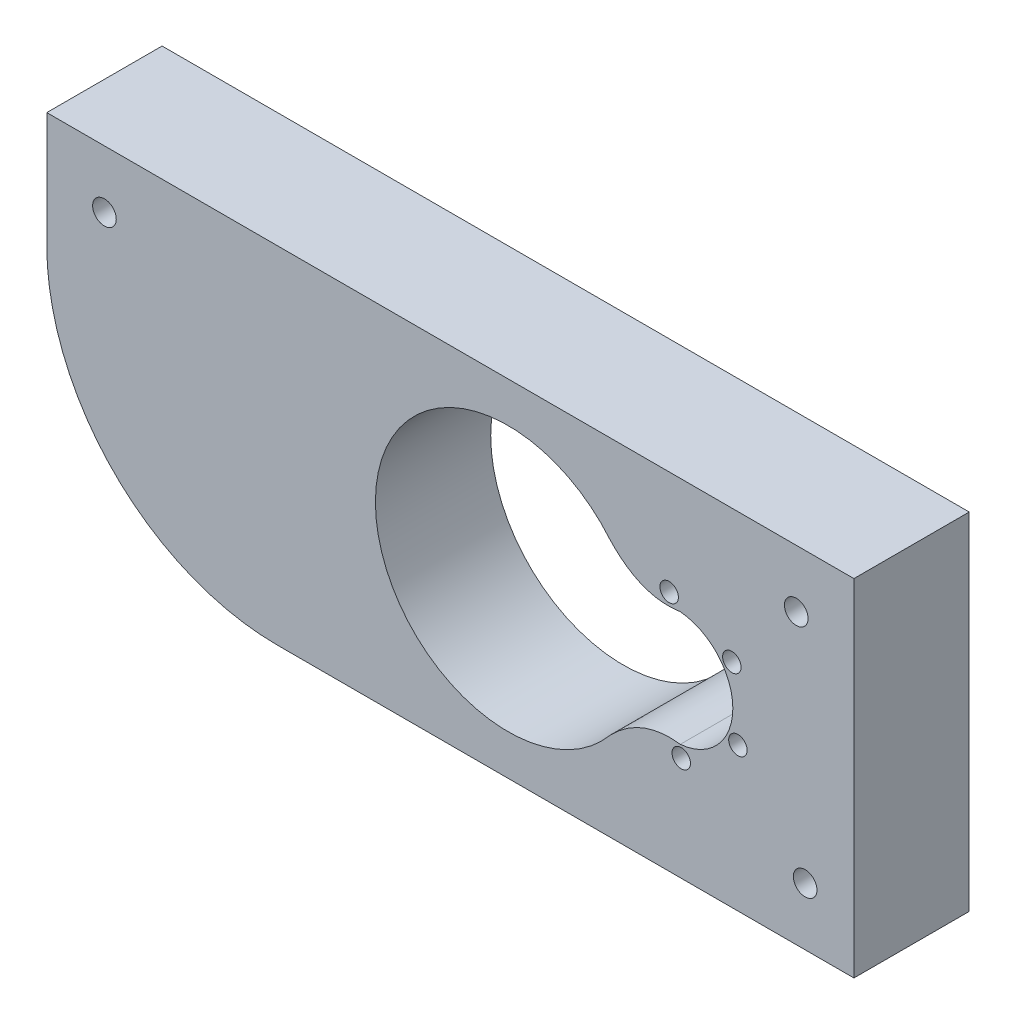
SolidWorks part; units mm, degrees
ref_plane "Plan de face" through (0, 0, 0) normal (0, 0, 1) x (1, 0, 0)
ref_plane "Plan de dessus" through (0, 0, 0) normal (0, 1, 0) x (1, 0, 0)
ref_plane "Plan de droite" through (0, 0, 0) normal (1, 0, 0) x (0, 0, -1)
sketch "Esquisse1" plane through (0, 0, 0) normal (0, 0, 1) x (1, 0, 0)
  line L1 (0, 0) -> (70, 0)
  line L2 (0, 0) -> (0, 30)
  line L3 (0, 30) -> (70, 30)
  line L4 (70, 0) -> (70, 30)
  dimension "D1" = 30
  dimension "D2" = 70
extrude "Boss.-Extru.1" add sketch "Esquisse1" along normal blind 10
sketch "Esquisse2" plane through (0, 0, 10) normal (0, 0, 1) x (1, 0, 0)
  line L0 (66.0915, 15) -> (-1.5751, 15) construction
  line L1 (54.5, 34.4565) -> (54.5, -6.8023) construction
  line L2 (70, 30) -> (0, 30) construction
  line L4 (0, 30) -> (0, 0) construction
  arc A0 (54.9408, 19.9805) -> (54.9408, 10.0195) centre (54.5, 15) cw
  circle A2 centre (53.9746, 20.9769) radius 0.8
  circle A3 centre (59.4135, 18.4435) radius 0.8
  circle A4 centre (59.9389, 12.4666) radius 0.8
  circle A5 centre (55.0254, 9.0231) radius 0.8
  arc A6 (48.86, 22.3315) -> (48.86, 7.6685) centre (40, 15) ccw
  circle A8 centre (49.0611, 17.5334) radius 0.8 [skipped]
  circle A9 centre (49.5865, 11.5565) radius 0.8 [skipped]
  spline S0 degree 2 poles (48.86, 22.3315) (51.5345, 19.4593) (54.9408, 19.9805) knots 0 0 0 1 1 1
  spline S1 degree 2 poles (48.86, 7.6685) (51.5403, 10.446) (54.9408, 10.0195) knots 0 0 0 1 1 1
  point P18 (54.5, 15)
  point P32 (59.5, 15)
  dimension "D1" = 11.5
  dimension "D2" = 5
  dimension "D3" = 1.6
  dimension "D5" = 14.5
  dimension "D8" = 10.64
  dimension "D6" = 15
  dimension "D7" = 40
  dimension "D9" = 10.64
  dimension "D10" = 8.86
  dimension "D11" = 4.7
  dimension "D12" = 4.7
  dimension "D13" = 5.9769
  dimension "D14" = 6
  dimension "D4" = 6
extrude "Enlèv. mat.-Extru.1" cut sketch "Esquisse2" against normal through all
sketch "Esquisse3" plane through (0, 0, 10) normal (0, 0, 1) x (1, 0, 0)
  line L1 (70, 0) -> (70, 30) construction
  line L2 (70, 30) -> (0, 30) construction
  circle A0 centre (5, 25) radius 1.025
  circle A2 centre (65.7711, 5) radius 1.025
  circle A3 centre (65, 25) radius 1.025
  dimension "D2" = 2.05
  dimension "D6" = 2.05
  dimension "D7" = 2.05
  dimension "D9" = 5
  dimension "D10" = 5
  dimension "D8" = 4.2289
extrude "Enlèv. mat.-Extru.2" cut sketch "Esquisse3" against normal through all
fillet "Congé2" radius 20 1 edges at (0, 0, 5)
